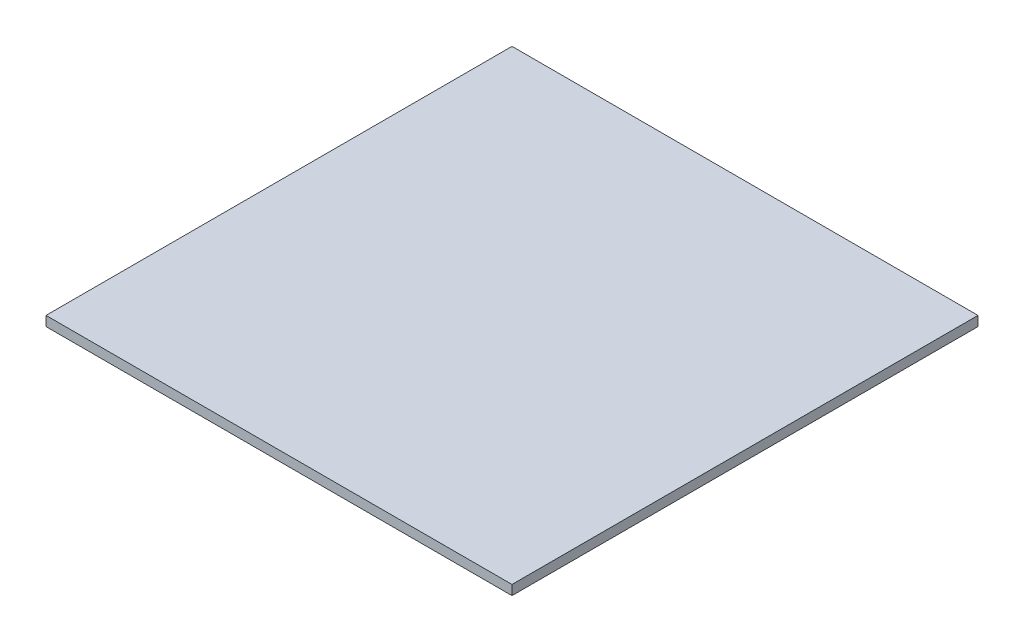
SolidWorks part; units mm, degrees
ref_plane "Front Plane" through (0, 0, 0) normal (0, 0, 1) x (1, 0, 0)
ref_plane "Top Plane" through (0, 0, 0) normal (0, 1, 0) x (1, 0, 0)
ref_plane "Right Plane" through (0, 0, 0) normal (1, 0, 0) x (0, 0, -1)
sketch "Sketch1" plane through (0, 0, 0) normal (0, 0, 1) x (1, 0, 0)
  line L0 (0, 1.5875) -> (0, -1.5875)
  line L1 (-76.2, 0) -> (76.2, 0) construction
  point P6 (0, 0)
  dimension "Width" = 152.4
  dimension "Thk" = 3.175
sketch "Sketch2" plane through (0, 0, 0) normal (1, 0, 0) x (0, 0, -1)
  line L0 (76.2, 0) -> (-76.2, 0)
  point P4 (0, 0)
  dimension "Length" = 152.4
sketch "Sketch3" plane through (0, 0, 0) normal (0, 0, 1) x (1, 0, 0)
  line L1 (76.2, 1.5875) -> (-76.2, 1.5875)
  line L2 (76.2, 1.5875) -> (76.2, -1.5875)
  line L3 (76.2, -1.5875) -> (-76.2, -1.5875)
  line L4 (-76.2, 1.5875) -> (-76.2, -1.5875)
  line L5 (76.2, 1.5875) -> (-76.2, -1.5875) construction
  line L6 (76.2, -1.5875) -> (-76.2, 1.5875) construction
  point P0 (0, 0)
extrude "Boss-Extrude1" add sketch "Sketch3" along normal up to vertex (76.2 mm away) and the other way up to vertex (76.2 mm away) up to point (0, 0, 76.2) other way up to point (0, 0, -76.2)
